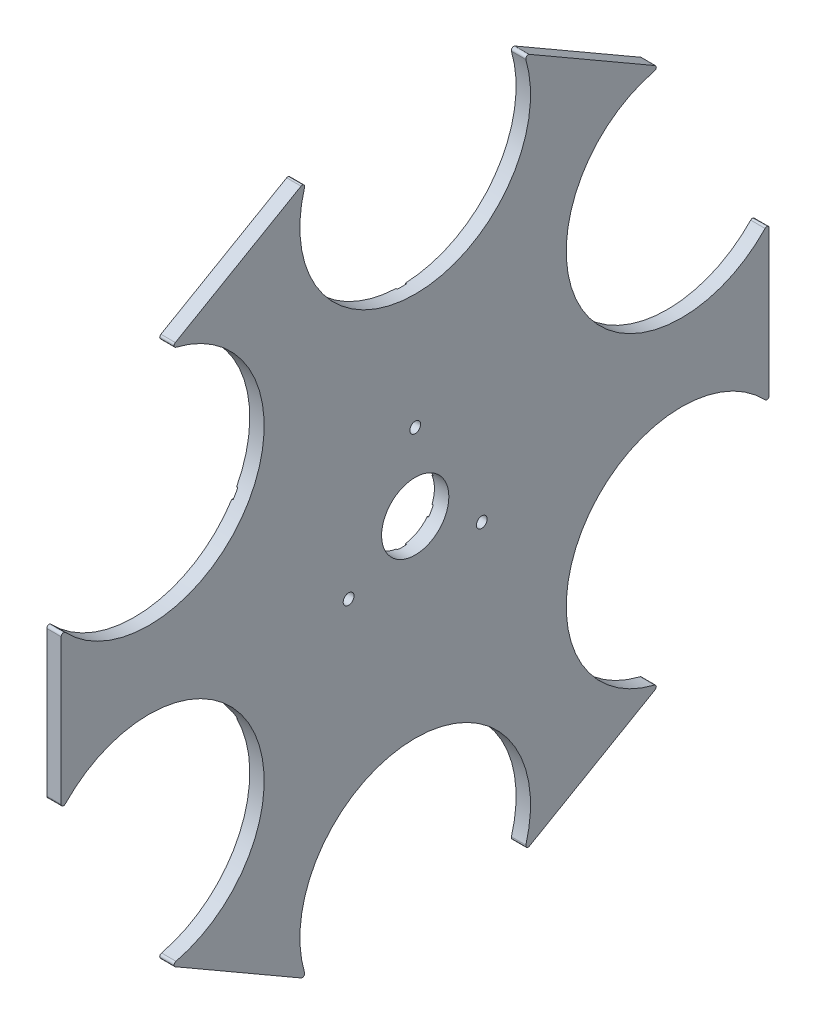
SolidWorks part; units mm, degrees
ref_plane "Front Plane" through (0, 0, 0) normal (0, 0, 1) x (1, 0, 0)
ref_plane "Top Plane" through (0, 0, 0) normal (0, 1, 0) x (1, 0, 0)
ref_plane "Right Plane" through (0, 0, 0) normal (1, 0, 0) x (0, 0, -1)
sketch "Sketch2" plane through (0, 0, 0) normal (1, 0, 0) x (0, 0, -1)
  line L0 (35.921, 114.3) -> (-35.921, 114.3) construction
  line L1 (81.0262, 88.2585) -> (35.921, 114.3)
  line L2 (116.9472, -26.0415) -> (116.9472, 26.0415)
  line L3 (35.921, -114.3) -> (81.0262, -88.2585)
  line L4 (-81.0262, -88.2585) -> (-35.921, -114.3)
  line L5 (-116.9472, 26.0415) -> (-116.9472, -26.0415)
  line L6 (-35.921, 114.3) -> (-81.0262, 88.2585)
  circle A0 centre (0, 0) radius 101.6 construction
  arc A1 (-35.921, 114.3) -> (35.921, 114.3) centre (0, 101.6) ccw
  arc A2 (81.0262, 88.2585) -> (116.9472, 26.0415) centre (87.9882, 50.8) ccw
  arc A3 (116.9472, -26.0415) -> (81.0262, -88.2585) centre (87.9882, -50.8) ccw
  arc A4 (35.921, -114.3) -> (-35.921, -114.3) centre (0, -101.6) ccw
  arc A5 (-81.0262, -88.2585) -> (-116.9472, -26.0415) centre (-87.9882, -50.8) ccw
  arc A6 (-116.9472, 26.0415) -> (-81.0262, 88.2585) centre (-87.9882, 50.8) ccw
  circle A7 centre (0, 0) radius 11.11
  point P23 (0, 0)
  point P34 (0, 0)
  dimension "D1" = 203.2
  dimension "D2" = 114.3
  dimension "D3" = 76.2
  dimension "D4" = 6
  dimension "D5" = 6
extrude "Boss-Extrude1" add sketch "Sketch2" along normal blind 4.7625
sketch "Sketch3" plane through (0, 0, 0) normal (-1, 0, 0) x (0, 0, 1)
  line L0 (1.5875, 10.6044) -> (-1.5875, 10.6044)
  line L1 (1.5875, 192.5956) -> (-1.5875, 192.5956)
  line L2 (1.5875, 192.5956) -> (1.5875, 10.6044)
  line L3 (167.5864, 94.923) -> (165.9989, 97.6726)
  line L4 (-1.5875, 192.5956) -> (-1.5875, 10.6044)
  line L5 (1.5875, 192.5956) -> (-1.5875, 10.6044) construction
  line L6 (1.5875, 10.6044) -> (-1.5875, 192.5956) construction
  line L7 (167.5864, 94.923) -> (9.9774, 3.9274)
  line L8 (165.9989, 97.6726) -> (8.3899, 6.677)
  line L9 (9.9774, 3.9274) -> (8.3899, 6.677)
  line L10 (165.9989, -97.6726) -> (167.5864, -94.923)
  line L11 (165.9989, -97.6726) -> (8.3899, -6.677)
  line L12 (167.5864, -94.923) -> (9.9774, -3.9274)
  line L13 (8.3899, -6.677) -> (9.9774, -3.9274)
  line L14 (-1.5875, -192.5956) -> (1.5875, -192.5956)
  line L15 (-1.5875, -192.5956) -> (-1.5875, -10.6044)
  line L16 (1.5875, -192.5956) -> (1.5875, -10.6044)
  line L17 (-1.5875, -10.6044) -> (1.5875, -10.6044)
  line L18 (-167.5864, -94.923) -> (-165.9989, -97.6726)
  line L19 (-167.5864, -94.923) -> (-9.9774, -3.9274)
  line L20 (-165.9989, -97.6726) -> (-8.3899, -6.677)
  line L21 (-9.9774, -3.9274) -> (-8.3899, -6.677)
  line L22 (-165.9989, 97.6726) -> (-167.5864, 94.923)
  line L23 (-165.9989, 97.6726) -> (-8.3899, 6.677)
  line L24 (-167.5864, 94.923) -> (-9.9774, 3.9274)
  line L25 (-8.3899, 6.677) -> (-9.9774, 3.9274)
  point P0 (0, 101.6)
  point P28 (0, 0)
  point P29 (0, 0)
  dimension "D1" = 3.175
  dimension "D2" = 6
extrude "Cut-Extrude1" cut sketch "Sketch3" against normal blind 0.3969
fillet "Fillet1" radius 0.7937 12 edges at (2.3813, -114.3, 35.921) (2.3813, -114.3, -35.921) (2.3813, -88.2585, -81.0262) (2.3813, -26.0415, -116.9472) (2.3813, 88.2585, -81.0262) (2.3813, 26.0415, -116.9472) (2.3813, -88.2585, 81.0262) (2.3813, -26.0415, 116.9472) (2.3813, 26.0415, 116.9472) (2.3813, 88.2585, 81.0262) (2.3813, 114.3, -35.921) (2.3813, 114.3, 35.921)
hole_wizard "9/64 (0.14063) Diameter Hole1" positions "Sketch7" profile "Sketch6" hole size "9/64" standard "ANSI Inch" end condition through all
sketch "Sketch7" plane through (0, 0, 0) normal (-1, 0, 0) x (0, 0, 1)
  line L0 (0, 0) -> (0, 25.4) construction
  line L1 (0, 0) -> (21.997, -12.7) construction
  line L2 (0, 0) -> (-21.997, -12.7) construction
  circle A0 centre (0, 0) radius 25.4
  point P5 (0, 25.4)
  point P10 (21.997, -12.7)
  point P13 (-21.997, -12.7)
  dimension "D1" = 120
  dimension "D2" = 120
sketch "Sketch6" plane through (0, 25.4, 0) normal (0, 1, 0) x (0, 0, 1)
  line L0 (0, 0) -> (0, 4.7625)
  line L1 (0, 4.7625) -> (1.786, 4.7625)
  line L2 (1.786, 4.7625) -> (1.786, 0)
  line L5 (1.786, 0) -> (0, 0)
  line L11 (0, -6.35) -> (0, 107.95) construction
  dimension "Thru Hole Dia." = 3.572
  dimension "Thru Hole Depth" = 4.7625
sketch "Sketch8" plane through (0, 0, 0) normal (-1, 0, 0) x (0, 0, 1)
  line L0 (0, 63.5) -> (0, 43.4086) construction
  line L1 (3.9687, 60.325) -> (3.9687, 53.975)
  line L2 (-3.9687, 60.325) -> (-7.1437, 60.325)
  line L3 (-3.9687, 60.325) -> (-3.9687, 53.975)
  line L4 (-3.9687, 53.975) -> (-7.1437, 53.975)
  line L5 (-7.1437, 60.325) -> (-7.1437, 53.975)
  line L6 (3.9687, 60.325) -> (7.1437, 60.325)
  line L7 (7.1437, 60.325) -> (7.1437, 53.975)
  line L8 (3.9687, 53.975) -> (7.1437, 53.975)
  line L9 (44.7593, 30.4245) -> (43.1718, 33.1742)
  line L10 (50.2586, 33.5995) -> (44.7593, 30.4245)
  line L11 (48.6711, 36.3492) -> (43.1718, 33.1742)
  line L12 (50.2586, 33.5995) -> (48.6711, 36.3492)
  line L13 (54.2274, 26.7255) -> (55.8149, 23.9758)
  line L14 (48.7281, 23.5505) -> (50.3156, 20.8008)
  line L15 (54.2274, 26.7255) -> (48.7281, 23.5505)
  line L16 (55.8149, 23.9758) -> (50.3156, 20.8008)
  line L17 (48.7281, -23.5505) -> (50.3156, -20.8008)
  line L18 (54.2274, -26.7255) -> (48.7281, -23.5505)
  line L19 (55.8149, -23.9758) -> (50.3156, -20.8008)
  line L20 (54.2274, -26.7255) -> (55.8149, -23.9758)
  line L21 (50.2586, -33.5995) -> (48.6711, -36.3492)
  line L22 (44.7593, -30.4245) -> (43.1718, -33.1742)
  line L23 (50.2586, -33.5995) -> (44.7593, -30.4245)
  line L24 (48.6711, -36.3492) -> (43.1718, -33.1742)
  line L25 (3.9688, -53.975) -> (7.1438, -53.975)
  line L26 (3.9688, -60.325) -> (3.9688, -53.975)
  line L27 (7.1438, -60.325) -> (7.1438, -53.975)
  line L28 (3.9688, -60.325) -> (7.1438, -60.325)
  line L29 (-3.9687, -60.325) -> (-7.1437, -60.325)
  line L30 (-3.9687, -53.975) -> (-7.1437, -53.975)
  line L31 (-3.9687, -60.325) -> (-3.9687, -53.975)
  line L32 (-7.1437, -60.325) -> (-7.1437, -53.975)
  line L33 (-44.7593, -30.4245) -> (-43.1718, -33.1742)
  line L34 (-50.2586, -33.5995) -> (-44.7593, -30.4245)
  line L35 (-48.6711, -36.3492) -> (-43.1718, -33.1742)
  line L36 (-50.2586, -33.5995) -> (-48.6711, -36.3492)
  line L37 (-54.2274, -26.7255) -> (-55.8149, -23.9758)
  line L38 (-48.7281, -23.5505) -> (-50.3156, -20.8008)
  line L39 (-54.2274, -26.7255) -> (-48.7281, -23.5505)
  line L40 (-55.8149, -23.9758) -> (-50.3156, -20.8008)
  line L41 (-48.7281, 23.5505) -> (-50.3156, 20.8008)
  line L42 (-54.2274, 26.7255) -> (-48.7281, 23.5505)
  line L43 (-55.8149, 23.9758) -> (-50.3156, 20.8008)
  line L44 (-54.2274, 26.7255) -> (-55.8149, 23.9758)
  line L45 (-50.2586, 33.5995) -> (-48.6711, 36.3492)
  line L46 (-44.7593, 30.4245) -> (-43.1718, 33.1742)
  line L47 (-50.2586, 33.5995) -> (-44.7593, 30.4245)
  line L48 (-48.6711, 36.3492) -> (-43.1718, 33.1742)
  arc A0 (-1.5875, 63.5331) -> (1.5875, 63.5331) centre (0, 101.6) ccw construction
  point P57 (0, 0)
  dimension "D1" = 3.175
  dimension "D2" = 6.35
  dimension "D3" = 3.9688
  dimension "D4" = 3.175
  dimension "D5" = 6
extrude "Cut-Extrude2" [suppressed] cut sketch "Sketch8" against normal through all
